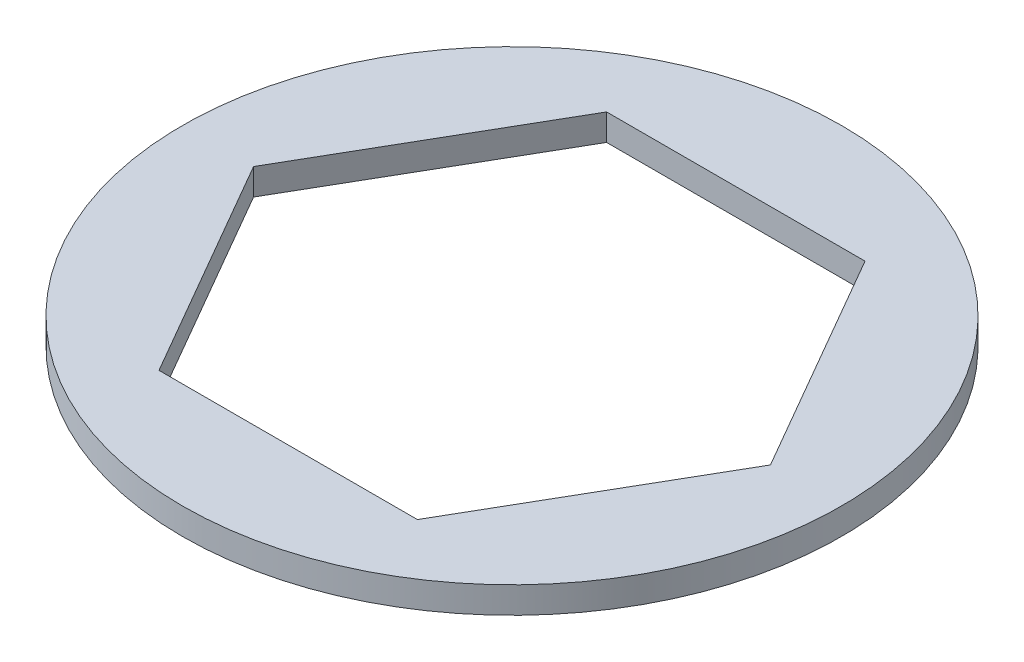
SolidWorks part; units mm, degrees
material "PET"
ref_plane "Front Plane" through (0, 0, 0) normal (0, 0, 1) x (1, 0, 0)
ref_plane "Top Plane" through (0, 0, 0) normal (0, 1, 0) x (1, 0, 0)
ref_plane "Right Plane" through (0, 0, 0) normal (1, 0, 0) x (0, 0, -1)
sketch "Sketch1" plane through (0, 0, 0) normal (0, 1, 0) x (1, 0, 0)
  line L7 (7.4497, 0) -> (3.7248, 6.4516)
  line L8 (3.7248, 6.4516) -> (-3.7248, 6.4516)
  line L9 (-3.7248, 6.4516) -> (-7.4497, 0)
  line L10 (-7.4497, 0) -> (-3.7248, -6.4516)
  line L11 (-3.7248, -6.4516) -> (3.7248, -6.4516)
  line L12 (3.7248, -6.4516) -> (7.4497, 0)
  circle A0 centre (0, 0) radius 6.4516 construction
  circle A7 centre (0, 0) radius 9.5
  dimension "D1" = 12.9032
  dimension "D2" = 19
extrude "Boss-Extrude1" add sketch "Sketch1" against normal blind 0.762
